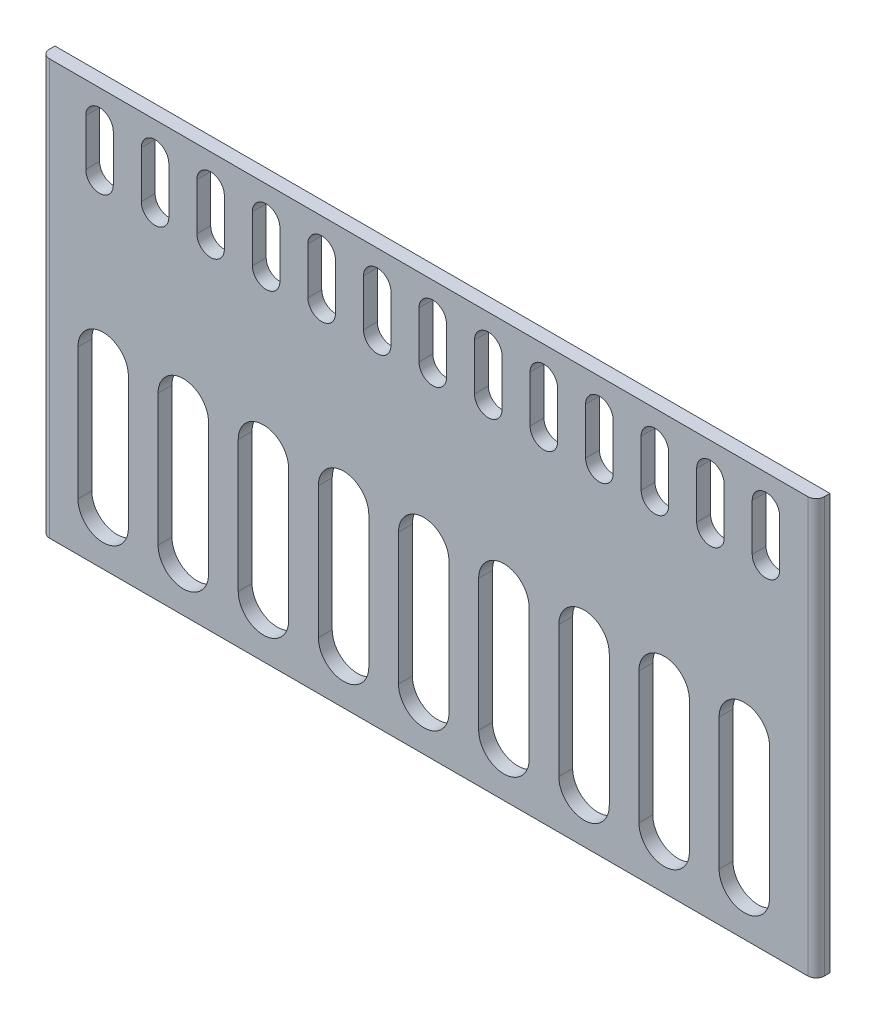
SolidWorks part; units mm, degrees
material "2024-T361"
ref_plane "Front Plane" through (0, 0, 0) normal (0, 0, 1) x (1, 0, 0)
ref_plane "Top Plane" through (0, 0, 0) normal (0, 1, 0) x (1, 0, 0)
ref_plane "Right Plane" through (0, 0, 0) normal (1, 0, 0) x (0, 0, -1)
sketch "Sketch1" plane through (0, 0, 0) normal (0, 0, 1) x (1, 0, 0)
  line L1 (0, -65) -> (-280, -65)
  line L2 (0, -65) -> (0, 85)
  line L3 (0, 85) -> (-280, 85)
  line L4 (-280, -65) -> (-280, 85)
extrude "Boss-Extrude1" add sketch "Sketch1" along normal blind 5
fillet "Fillet1" radius 3 2 edges at (-280, 10, 5) (0, 10, 5)
sketch "Sketch2" plane through (0, 0, 5) normal (0, 0, 1) x (1, 0, 0)
  line L0 (-258.9148, 73.8126) -> (-258.9148, 56.9194) construction
  line L1 (-253.9463, 73.8126) -> (-253.9463, 56.9194)
  line L2 (-263.8834, 73.8126) -> (-263.8834, 56.9194)
  line L3 (-238.8488, 73.8126) -> (-238.8488, 56.9194) construction
  line L4 (-233.8803, 73.8126) -> (-233.8803, 56.9194)
  line L5 (-243.8174, 73.8126) -> (-243.8174, 56.9194)
  line L6 (-218.7828, 73.8126) -> (-218.7828, 56.9194) construction
  line L7 (-213.8143, 73.8126) -> (-213.8143, 56.9194)
  line L8 (-223.7514, 73.8126) -> (-223.7514, 56.9194)
  line L9 (-198.7168, 73.8126) -> (-198.7168, 56.9194) construction
  line L10 (-193.7483, 73.8126) -> (-193.7483, 56.9194)
  line L11 (-203.6854, 73.8126) -> (-203.6854, 56.9194)
  line L12 (-178.6508, 73.8126) -> (-178.6508, 56.9194) construction
  line L13 (-173.6823, 73.8126) -> (-173.6823, 56.9194)
  line L14 (-183.6194, 73.8126) -> (-183.6194, 56.9194)
  line L15 (-158.5848, 73.8126) -> (-158.5848, 56.9194) construction
  line L16 (-153.6163, 73.8126) -> (-153.6163, 56.9194)
  line L17 (-163.5534, 73.8126) -> (-163.5534, 56.9194)
  line L18 (-138.5188, 73.8126) -> (-138.5188, 56.9194) construction
  line L19 (-133.5503, 73.8126) -> (-133.5503, 56.9194)
  line L20 (-143.4874, 73.8126) -> (-143.4874, 56.9194)
  line L21 (-118.4528, 73.8126) -> (-118.4528, 56.9194) construction
  line L22 (-113.4843, 73.8126) -> (-113.4843, 56.9194)
  line L23 (-123.4214, 73.8126) -> (-123.4214, 56.9194)
  line L24 (-98.3868, 73.8126) -> (-98.3868, 56.9194) construction
  line L25 (-93.4183, 73.8126) -> (-93.4183, 56.9194)
  line L26 (-103.3554, 73.8126) -> (-103.3554, 56.9194)
  line L27 (-78.3208, 73.8126) -> (-78.3208, 56.9194) construction
  line L28 (-73.3523, 73.8126) -> (-73.3523, 56.9194)
  line L29 (-83.2894, 73.8126) -> (-83.2894, 56.9194)
  line L30 (-58.2548, 73.8126) -> (-58.2548, 56.9194) construction
  line L31 (-53.2863, 73.8126) -> (-53.2863, 56.9194)
  line L32 (-63.2234, 73.8126) -> (-63.2234, 56.9194)
  line L33 (-38.1888, 73.8126) -> (-38.1888, 56.9194) construction
  line L34 (-33.2203, 73.8126) -> (-33.2203, 56.9194)
  line L35 (-43.1574, 73.8126) -> (-43.1574, 56.9194)
  line L36 (-18.1228, 73.8126) -> (-18.1228, 56.9194) construction
  line L37 (-13.1543, 73.8126) -> (-13.1543, 56.9194)
  line L38 (-23.0914, 73.8126) -> (-23.0914, 56.9194)
  line L39 (-258.9148, 73.8126) -> (-238.8488, 73.8126) construction
  arc A0 (-253.9463, 73.8126) -> (-263.8834, 73.8126) centre (-258.9148, 73.8126) ccw
  arc A1 (-263.8834, 56.9194) -> (-253.9463, 56.9194) centre (-258.9148, 56.9194) ccw
  arc A2 (-233.8803, 73.8126) -> (-243.8174, 73.8126) centre (-238.8488, 73.8126) ccw
  arc A3 (-243.8174, 56.9194) -> (-233.8803, 56.9194) centre (-238.8488, 56.9194) ccw
  arc A4 (-213.8143, 73.8126) -> (-223.7514, 73.8126) centre (-218.7828, 73.8126) ccw
  arc A5 (-223.7514, 56.9194) -> (-213.8143, 56.9194) centre (-218.7828, 56.9194) ccw
  arc A6 (-193.7483, 73.8126) -> (-203.6854, 73.8126) centre (-198.7168, 73.8126) ccw
  arc A7 (-203.6854, 56.9194) -> (-193.7483, 56.9194) centre (-198.7168, 56.9194) ccw
  arc A8 (-173.6823, 73.8126) -> (-183.6194, 73.8126) centre (-178.6508, 73.8126) ccw
  arc A9 (-183.6194, 56.9194) -> (-173.6823, 56.9194) centre (-178.6508, 56.9194) ccw
  arc A10 (-153.6163, 73.8126) -> (-163.5534, 73.8126) centre (-158.5848, 73.8126) ccw
  arc A11 (-163.5534, 56.9194) -> (-153.6163, 56.9194) centre (-158.5848, 56.9194) ccw
  arc A12 (-133.5503, 73.8126) -> (-143.4874, 73.8126) centre (-138.5188, 73.8126) ccw
  arc A13 (-143.4874, 56.9194) -> (-133.5503, 56.9194) centre (-138.5188, 56.9194) ccw
  arc A14 (-113.4843, 73.8126) -> (-123.4214, 73.8126) centre (-118.4528, 73.8126) ccw
  arc A15 (-123.4214, 56.9194) -> (-113.4843, 56.9194) centre (-118.4528, 56.9194) ccw
  arc A16 (-93.4183, 73.8126) -> (-103.3554, 73.8126) centre (-98.3868, 73.8126) ccw
  arc A17 (-103.3554, 56.9194) -> (-93.4183, 56.9194) centre (-98.3868, 56.9194) ccw
  arc A18 (-73.3523, 73.8126) -> (-83.2894, 73.8126) centre (-78.3208, 73.8126) ccw
  arc A19 (-83.2894, 56.9194) -> (-73.3523, 56.9194) centre (-78.3208, 56.9194) ccw
  arc A20 (-53.2863, 73.8126) -> (-63.2234, 73.8126) centre (-58.2548, 73.8126) ccw
  arc A21 (-63.2234, 56.9194) -> (-53.2863, 56.9194) centre (-58.2548, 56.9194) ccw
  arc A22 (-33.2203, 73.8126) -> (-43.1574, 73.8126) centre (-38.1888, 73.8126) ccw
  arc A23 (-43.1574, 56.9194) -> (-33.2203, 56.9194) centre (-38.1888, 56.9194) ccw
  arc A24 (-13.1543, 73.8126) -> (-23.0914, 73.8126) centre (-18.1228, 73.8126) ccw
  arc A25 (-23.0914, 56.9194) -> (-13.1543, 56.9194) centre (-18.1228, 56.9194) ccw
  point P2 (-258.9148, 65.366)
  point P11 (-238.8488, 65.366)
  point P18 (-218.7828, 65.366)
  point P25 (-198.7168, 65.366)
  point P32 (-178.6508, 65.366)
  point P39 (-158.5848, 65.366)
  point P46 (-138.5188, 65.366)
  point P53 (-118.4528, 65.366)
  point P60 (-98.3868, 65.366)
  point P67 (-78.3208, 65.366)
  point P74 (-58.2548, 65.366)
  point P81 (-38.1888, 65.366)
  point P88 (-18.1228, 65.366)
  dimension "D1" = 20.066
extrude "Cut-Extrude1" cut sketch "Sketch2" against normal up to next
sketch "Sketch3" plane through (0, 0, 5) normal (0, 0, 1) x (1, 0, 0)
  line L0 (-257.5925, 0) -> (-257.5925, -47.5534) construction
  line L1 (-248.4802, 0) -> (-248.4802, -47.5534)
  line L2 (-266.7049, 0) -> (-266.7049, -47.5534)
  line L3 (-228.6365, 0) -> (-228.6365, -47.5534) construction
  line L4 (-219.5242, 0) -> (-219.5242, -47.5534)
  line L5 (-237.7489, 0) -> (-237.7489, -47.5534)
  line L6 (-199.6805, 0) -> (-199.6805, -47.5534) construction
  line L7 (-190.5682, 0) -> (-190.5682, -47.5534)
  line L8 (-208.7929, 0) -> (-208.7929, -47.5534)
  line L9 (-170.7245, 0) -> (-170.7245, -47.5534) construction
  line L10 (-161.6122, 0) -> (-161.6122, -47.5534)
  line L11 (-179.8369, 0) -> (-179.8369, -47.5534)
  line L12 (-141.7685, 0) -> (-141.7685, -47.5534) construction
  line L13 (-132.6562, 0) -> (-132.6562, -47.5534)
  line L14 (-150.8809, 0) -> (-150.8809, -47.5534)
  line L15 (-112.8125, 0) -> (-112.8125, -47.5534) construction
  line L16 (-103.7002, 0) -> (-103.7002, -47.5534)
  line L17 (-121.9249, 0) -> (-121.9249, -47.5534)
  line L18 (-83.8565, 0) -> (-83.8565, -47.5534) construction
  line L19 (-74.7442, 0) -> (-74.7442, -47.5534)
  line L20 (-92.9689, 0) -> (-92.9689, -47.5534)
  line L21 (-54.9005, 0) -> (-54.9005, -47.5534) construction
  line L22 (-45.7882, 0) -> (-45.7882, -47.5534)
  line L23 (-64.0129, 0) -> (-64.0129, -47.5534)
  line L24 (-25.9445, 0) -> (-25.9445, -47.5534) construction
  line L25 (-16.8322, 0) -> (-16.8322, -47.5534)
  line L26 (-35.0569, 0) -> (-35.0569, -47.5534)
  line L27 (-257.5925, 0) -> (-228.6365, 0) construction
  arc A0 (-248.4802, 0) -> (-266.7049, 0) centre (-257.5925, 0) ccw
  arc A1 (-266.7049, -47.5534) -> (-248.4802, -47.5534) centre (-257.5925, -47.5534) ccw
  arc A2 (-219.5242, 0) -> (-237.7489, 0) centre (-228.6365, 0) ccw
  arc A3 (-237.7489, -47.5534) -> (-219.5242, -47.5534) centre (-228.6365, -47.5534) ccw
  arc A4 (-190.5682, 0) -> (-208.7929, 0) centre (-199.6805, 0) ccw
  arc A5 (-208.7929, -47.5534) -> (-190.5682, -47.5534) centre (-199.6805, -47.5534) ccw
  arc A6 (-161.6122, 0) -> (-179.8369, 0) centre (-170.7245, 0) ccw
  arc A7 (-179.8369, -47.5534) -> (-161.6122, -47.5534) centre (-170.7245, -47.5534) ccw
  arc A8 (-132.6562, 0) -> (-150.8809, 0) centre (-141.7685, 0) ccw
  arc A9 (-150.8809, -47.5534) -> (-132.6562, -47.5534) centre (-141.7685, -47.5534) ccw
  arc A10 (-103.7002, 0) -> (-121.9249, 0) centre (-112.8125, 0) ccw
  arc A11 (-121.9249, -47.5534) -> (-103.7002, -47.5534) centre (-112.8125, -47.5534) ccw
  arc A12 (-74.7442, 0) -> (-92.9689, 0) centre (-83.8565, 0) ccw
  arc A13 (-92.9689, -47.5534) -> (-74.7442, -47.5534) centre (-83.8565, -47.5534) ccw
  arc A14 (-45.7882, 0) -> (-64.0129, 0) centre (-54.9005, 0) ccw
  arc A15 (-64.0129, -47.5534) -> (-45.7882, -47.5534) centre (-54.9005, -47.5534) ccw
  arc A16 (-16.8322, 0) -> (-35.0569, 0) centre (-25.9445, 0) ccw
  arc A17 (-35.0569, -47.5534) -> (-16.8322, -47.5534) centre (-25.9445, -47.5534) ccw
  point P2 (-257.5925, -23.7767)
  point P10 (-228.6365, -23.7767)
  point P17 (-199.6805, -23.7767)
  point P24 (-170.7245, -23.7767)
  point P31 (-141.7685, -23.7767)
  point P38 (-112.8125, -23.7767)
  point P45 (-83.8565, -23.7767)
  point P52 (-54.9005, -23.7767)
  point P59 (-25.9445, -23.7767)
  dimension "D1" = 28.956
extrude "Cut-Extrude2" cut sketch "Sketch3" against normal up to next
